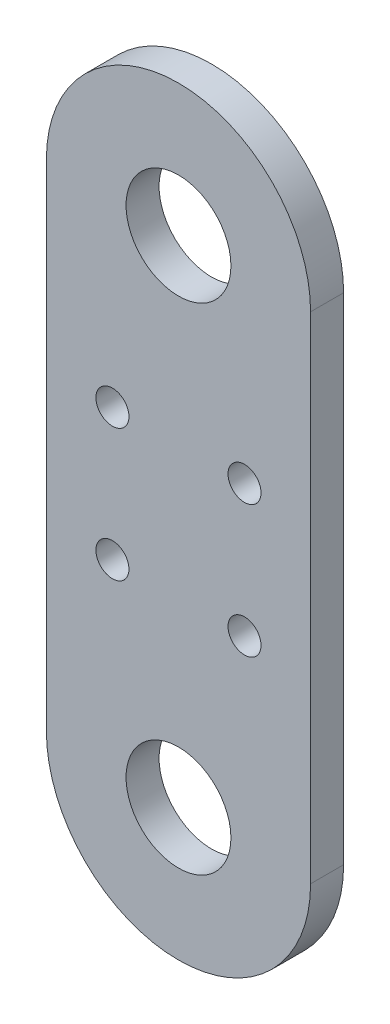
SolidWorks part; units mm, degrees
material "6061 Alloy"
ref_plane "Front" through (0, 0, 0) normal (0, 0, 1) x (1, 0, 0)
ref_plane "Top" through (0, 0, 0) normal (0, 1, 0) x (1, 0, 0)
ref_plane "Right" through (0, 0, 0) normal (1, 0, 0) x (0, 0, -1)
sketch "Sketch1" plane through (0, 0, 0) normal (0, 0, 1) x (1, 0, 0)
  line L0 (0, -23.8125) -> (0, 23.8125) construction
  line L1 (-12.7, -23.8125) -> (-12.7, 23.8125)
  line L2 (12.7, -23.8125) -> (12.7, 23.8125)
  arc A0 (-12.7, -23.8125) -> (12.7, -23.8125) centre (0, -23.8125) ccw
  arc A1 (12.7, 23.8125) -> (-12.7, 23.8125) centre (0, 23.8125) ccw
  point P2 (0, 0)
  dimension "D1" = 47.625
  dimension "D2" = 25.4
extrude "Boss-Extrude1" add sketch "Sketch1" along normal blind 3.175
hole_wizard "3/8 Clearance Hole2" positions "Sketch4" profile "Sketch5" hole size "3/8" standard "ANSI Inch" end condition through all
sketch "Sketch4" plane through (0, 0, 3.175) normal (0, 0, 1) x (1, 0, 0)
  point P0 (0, 23.8125)
  point P3 (0, -23.8125)
sketch "Sketch5" plane through (0, 23.8125, 3.175) normal (1, 0, 0) x (0, -1, 0)
  line L0 (0, 0) -> (0, 3.175)
  line L1 (0, 3.175) -> (5.0419, 3.175)
  line L2 (5.0419, 3.175) -> (5.0419, 0)
  line L5 (5.0419, 0) -> (0, 0)
  line L11 (0, -6.35) -> (0, 107.95) construction
  dimension "Thru Hole Dia." = 10.0838
  dimension "Thru Hole Depth" = 3.175
hole_wizard "1/8 (0.125) Diameter Hole1" positions "Sketch6" profile "Sketch7" hole size "1/8" standard "ANSI Inch" end condition through all
sketch "Sketch6" plane through (0, 0, 3.175) normal (0, 0, 1) x (1, 0, 0)
  line L0 (-12.7, 0) -> (12.7, 0) construction
  line L1 (-12.7, 23.8125) -> (-12.7, -23.8125) construction
  line L2 (12.7, -23.8125) -> (12.7, 23.8125) construction
  line L4 (-6.35, -6.35) -> (6.35, -6.35) construction
  line L5 (-6.35, -6.35) -> (-6.35, 6.35) construction
  line L6 (-6.35, 6.35) -> (6.35, 6.35) construction
  line L7 (6.35, -6.35) -> (6.35, 6.35) construction
  line L8 (-6.35, -6.35) -> (6.35, 6.35) construction
  line L9 (-6.35, 6.35) -> (6.35, -6.35) construction
  point P17 (6.35, 6.35)
  point P56 (-6.35, -6.35)
  point P57 (-6.35, 6.35)
  point P58 (6.35, -6.35)
  dimension "D1" = 12.7
sketch "Sketch7" plane through (6.35, -6.35, 3.175) normal (1, 0, 0) x (0, -1, 0)
  line L0 (0, 0) -> (0, 3.175)
  line L1 (0, 3.175) -> (1.5875, 3.175)
  line L2 (1.5875, 3.175) -> (1.5875, 0)
  line L5 (1.5875, 0) -> (0, 0)
  line L11 (0, -6.35) -> (0, 107.95) construction
  dimension "Thru Hole Dia." = 3.175
  dimension "Thru Hole Depth" = 3.175
hole_wizard "Tap Drill for #10-32 Tap1" positions "Sketch8" profile "Sketch9" hole size "#10-32" standard "ANSI Inch"
sketch "Sketch8" plane through (0, 0, 3.175) normal (0, 0, 1) x (1, 0, 0)
  point P0 (0, 0)
sketch "Sketch9" plane through (0, 0, 3.175) normal (1, 0, 0) x (0, -1, 0)
  line L0 (0, 0) -> (0, 3.175)
  line L1 (0, 3.175) -> (2.0193, 3.175)
  line L2 (2.0193, 3.175) -> (2.0193, 0)
  line L5 (2.0193, 0) -> (0, 0)
  line L11 (0, -6.35) -> (0, 107.95) construction
  dimension "Thru Hole Dia." = 4.0386
  dimension "Thru Hole Depth" = 3.175
